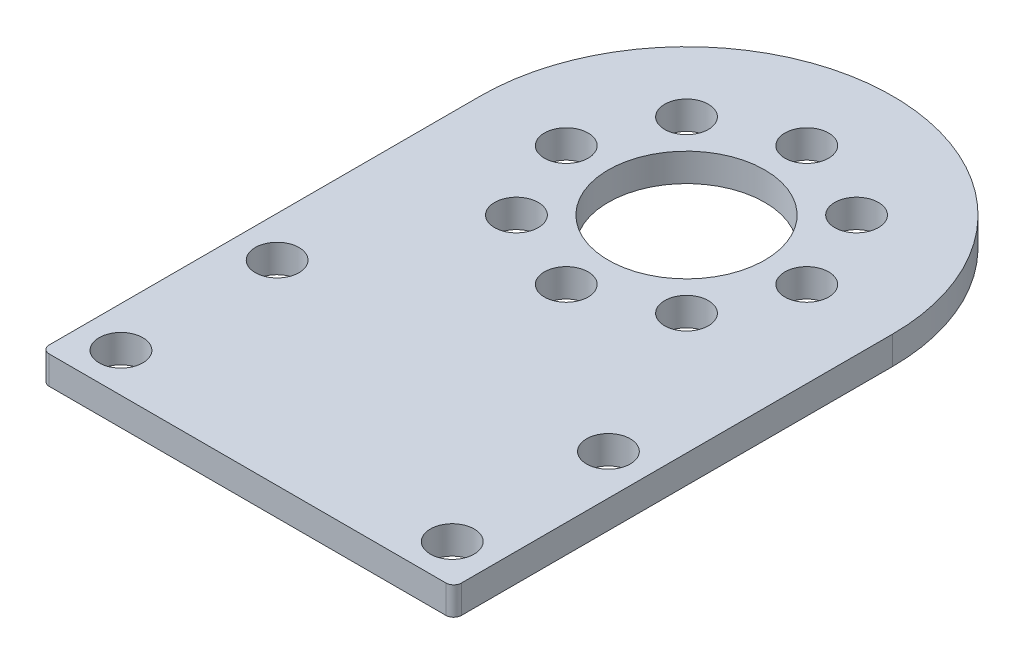
SolidWorks part; units mm, degrees
ref_plane "Front Plane" through (0, 0, 0) normal (0, 0, 1) x (1, 0, 0)
ref_plane "Top Plane" through (0, 0, 0) normal (0, 1, 0) x (1, 0, 0)
ref_plane "Right Plane" through (0, 0, 0) normal (1, 0, 0) x (0, 0, -1)
ref_plane "Plane1" through (0, 2.286, 0) normal (0, 1, 0) x (1, 0, 0)
sketch "Sketch1" plane through (0, 2.286, 0) normal (0, 1, 0) x (1, 0, 0)
  line L0 (16.764, -35.0604) -> (16.764, 0)
  line L1 (-16.764, 0) -> (-16.764, -35.0604)
  line L2 (-16.129, -35.6954) -> (16.129, -35.6954)
  arc A0 (16.764, 0) -> (-16.764, 0) centre (0, 0) ccw
  arc A1 (-16.764, -35.0604) -> (-16.129, -35.6954) centre (-16.129, -35.0604) ccw
  arc A2 (16.129, -35.6954) -> (16.764, -35.0604) centre (16.129, -35.0604) ccw
  circle A3 centre (0, 0) radius 6.3627
  circle A4 centre (9.779, 0) radius 1.778
  circle A5 centre (6.9148, 6.9148) radius 1.778
  circle A6 centre (0, 9.779) radius 1.778
  circle A7 centre (-6.9148, 6.9148) radius 1.778
  circle A8 centre (-9.779, 0) radius 1.778
  circle A9 centre (-6.9148, -6.9148) radius 1.778
  circle A10 centre (0, -9.779) radius 1.778
  circle A11 centre (6.9148, -6.9148) radius 1.778
  circle A12 centre (13.4704, -32.5204) radius 1.778
  circle A13 centre (-13.4704, -32.5204) radius 1.778
extrude "Boss-Extrude1" add sketch "Sketch1" against normal blind 2.286
sketch "Sketch2" plane through (0, 2.286, 0) normal (0, 1, 0) x (1, 0, 0)
  circle A0 centre (13.4704, -19.8204) radius 1.778
  circle A1 centre (13.4704, -32.5204) radius 1.778 construction
  circle A2 centre (-13.4704, -19.8204) radius 1.778
  circle A3 centre (-13.4704, -32.5204) radius 1.778 construction
  dimension "D1" = 3.556
  dimension "D3" = 3.556
  dimension "D2" = 12.7
  dimension "D4" = 12.7
extrude "Cut-Extrude1" cut sketch "Sketch2" against normal blind 7.62
